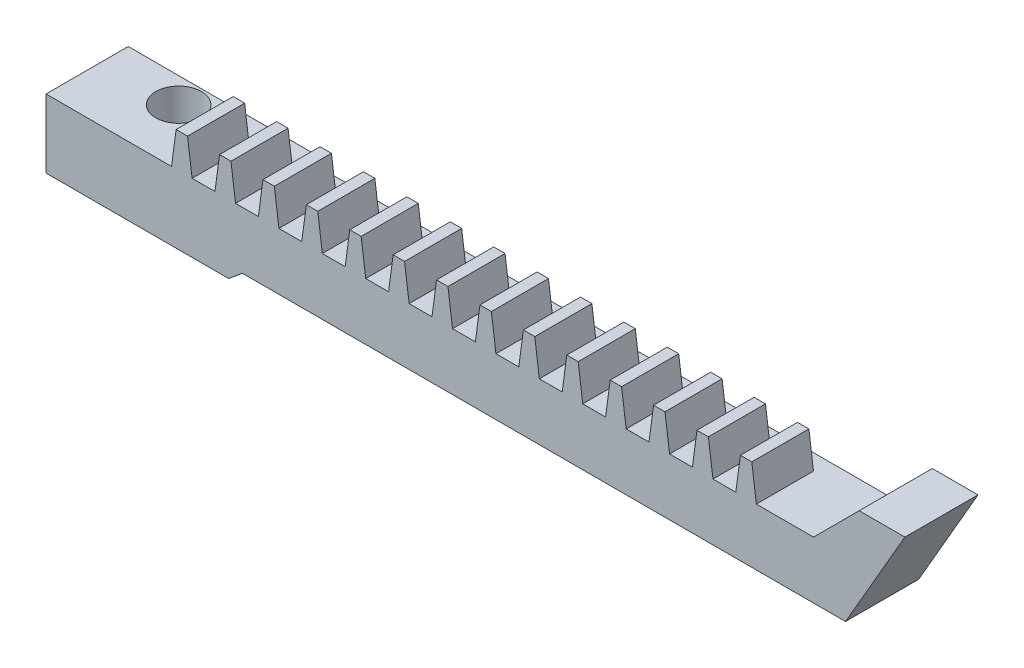
SolidWorks part; units mm, degrees
material "Plain Carbon Steel"
ref_plane "Front Plane" through (0, 0, 0) normal (0, 0, 1) x (1, 0, 0)
ref_plane "Top Plane" through (0, 0, 0) normal (0, 1, 0) x (1, 0, 0)
ref_plane "Right Plane" through (0, 0, 0) normal (1, 0, 0) x (0, 0, -1)
sketch "Sketch1" plane through (0, 0, 0) normal (0, 0, 1) x (1, 0, 0)
  line L0 (0, 0) -> (167.9904, 0)
  line L1 (167.9904, 0) -> (177.9904, 10)
  line L2 (0, 0) -> (0, -15)
  line L3 (0, -15) -> (40, -15)
  line L4 (40, -15) -> (42.9794, -12.5)
  line L5 (42.9794, -12.5) -> (175, -12.5)
  line L6 (175, -12.5) -> (187.9904, 10)
  line L7 (187.9904, 10) -> (177.9904, 10)
  dimension "D1" = 15
  dimension "D2" = 15
  dimension "D3" = 2.5
  dimension "D4" = 10
  dimension "D5" = 140
  dimension "D6" = 22.5
  dimension "D7" = 175
  dimension "D8" = 40
  dimension "D9" = 60
extrude "Boss-Extrude1" add sketch "Sketch1" along normal blind 18
sketch "Sketch6" plane through (0, 0, 0) normal (0, 1, 0) x (1, 0, 0)
  line L0 (187.9904, 0) -> (187.9904, -2)
  line L1 (187.9904, -18) -> (187.9904, 0) construction
  line L2 (187.9904, -2) -> (42.9794, -2)
  line L3 (42.9794, -2) -> (40, 0)
  line L4 (167.9904, 0) -> (0, 0) construction
  line L5 (40, 0) -> (187.9904, 0)
  dimension "D1" = 2
extrude "Cut-Extrude3" cut sketch "Sketch6" against normal through all from surface at 10 starting at face at (182.9904, 10, 9)
sketch "Sketch3" plane through (0, 0, 18) normal (0, 0, 1) x (1, 0, 0)
  line L0 (46.4794, 0) -> (50.9794, 0)
  line L1 (167.9904, 0) -> (0, 0) construction
  line L2 (50.9794, 0) -> (49.9794, 7.5)
  line L3 (49.9794, 7.5) -> (47.4794, 7.5)
  line L4 (47.4794, 7.5) -> (46.4794, 0)
  dimension "D1" = 4.5
  dimension "D2" = 2.5
  dimension "D3" = 7.5
  dimension "D4" = 3.5
extrude "Boss-Extrude2" add sketch "Sketch3" against normal blind 12.5
pattern_linear "LPattern1" count 12 spacing 9.5 along (1, 0, 0) count 3 spacing 9.5 along (-1, 0, 0) of "Boss-Extrude2"
sketch "Sketch5" plane through (0, -15, 0) normal (0, -1, 0) x (1, 0, 0)
  line L0 (0, 18) -> (0, 0) construction
  line L1 (40, 0) -> (0, 0) construction
  circle A0 centre (16.55, 5.5201) radius 5
  dimension "D1" = 10
  dimension "D2" = 16.55
  dimension "D3" = 5.5201
extrude "Cut-Extrude2" cut sketch "Sketch5" against normal through all both and the other way through all
